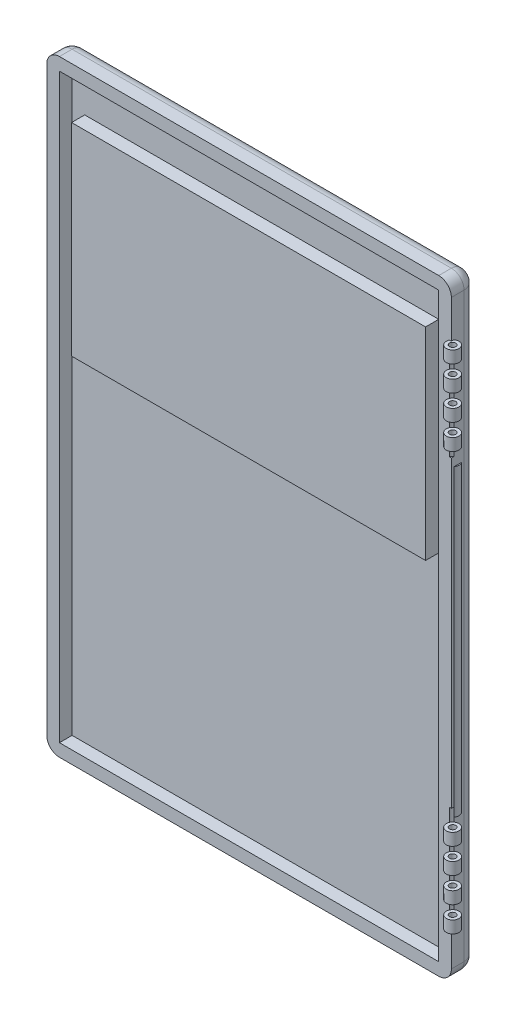
SolidWorks part; units mm, degrees
ref_plane "Frontal Plane" through (0, 0, 0) normal (0, 0, 1) x (1, 0, 0)
ref_plane "Horizontal Plane" through (0, 0, 0) normal (0, 1, 0) x (1, 0, 0)
ref_plane "Profile Plane" through (0, 0, 0) normal (1, 0, 0) x (0, 0, -1)
sketch "Sketch1" plane through (0, 0, 0) normal (0, 0, 1) x (1, 0, 0)
  line L1 (101.6, -152.4) -> (-101.6, -152.4)
  line L2 (101.6, -152.4) -> (101.6, 152.4)
  line L3 (101.6, 152.4) -> (-101.6, 152.4)
  line L4 (-101.6, -152.4) -> (-101.6, 152.4)
  line L5 (101.6, -152.4) -> (-101.6, 152.4) construction
  line L6 (101.6, 152.4) -> (-101.6, -152.4) construction
  point P0 (0, 0)
  dimension "D1" = 203.2
  dimension "D2" = 304.8
extrude "Boss-Extrude1" add sketch "Sketch1" against normal blind 12.7
ref_plane "Plane5" through (0, 0, 1.27) normal (0, 0, 1) x (1, 0, 0)
fillet "Fillet1" radius 6.35 8 edges at (-101.6, -152.4, -6.35) (0, -152.4, -12.7) (101.6, -152.4, -6.35) (-101.6, 0, -12.7) (101.6, 152.4, -6.35) (101.6, 0, -12.7) (-101.6, 152.4, -6.35) (0, 152.4, -12.7)
sketch "Sketch2" plane through (0, 0, 0) normal (0, 0, 1) x (1, 0, 0)
  line L0 (95.25, 152.4) -> (-95.25, 152.4) construction
  line L1 (95.25, -146.05) -> (-95.25, -146.05)
  line L2 (95.25, -146.05) -> (95.25, 146.05)
  line L3 (95.25, 146.05) -> (-95.25, 146.05)
  line L4 (-95.25, -146.05) -> (-95.25, 146.05)
  line L5 (95.25, -146.05) -> (-95.25, 146.05) construction
  line L6 (95.25, 146.05) -> (-95.25, -146.05) construction
  line L7 (-101.6, 146.05) -> (-101.6, -146.05) construction
  point P0 (0, 0)
  dimension "D1" = 6.35
  dimension "D2" = 6.35
extrude "Cut-Extrude1" cut sketch "Sketch2" against normal blind 6.35
sketch "Sketch3" plane through (0, 0, 0) normal (0, 1, 0) x (1, 0, 0)
  line L0 (95.25, 0) -> (101.6, 0) construction
  circle A0 centre (103.505, -1.27) radius 3.175
  dimension "D1" = 6.35
  dimension "D2" = 1.27
  dimension "D3" = 103.505
extrude "Boss-Extrude3" add sketch "Sketch3" along normal mid plane 254
sketch "Sketch14" plane through (0, 127, 0) normal (0, 1, 0) x (1, 0, 0)
  circle A0 centre (103.505, -1.27) radius 1.5875
  circle A1 centre (103.505, -1.27) radius 3.175 construction
  dimension "D1" = 3.175
extrude "Cut-Extrude9" cut sketch "Sketch14" against normal offset from surface (252.73 mm away) 1.27 up to face at (102.8974, -127, 0.8684)
sketch "Sketch6" plane through (0, 0, 1.27) normal (0, 0, 1) x (1, 0, 0)
  line L0 (106.68, -127) -> (106.68, 127) construction
  line L1 (103.505, 120.904) -> (106.68, 120.904)
  line L2 (103.505, 120.904) -> (103.505, 114.3)
  line L3 (103.505, 114.3) -> (106.68, 114.3)
  line L4 (106.68, 120.904) -> (106.68, 114.3)
  line L5 (103.505, 132.7034) -> (103.505, -150.9112) construction
  line L6 (103.505, -95.504) -> (106.68, -95.504)
  line L7 (103.505, 108.204) -> (106.68, 108.204)
  line L8 (103.505, 108.204) -> (103.505, 101.6)
  line L9 (103.505, 101.6) -> (106.68, 101.6)
  line L10 (106.68, 108.204) -> (106.68, 101.6)
  line L11 (103.505, 95.504) -> (106.68, 95.504)
  line L12 (103.505, 95.504) -> (103.505, 88.9)
  line L13 (103.505, 88.9) -> (106.68, 88.9)
  line L14 (106.68, 95.504) -> (106.68, 88.9)
  line L15 (103.505, -120.904) -> (106.68, -120.904)
  line L16 (103.505, -120.904) -> (103.505, -114.3)
  line L17 (103.505, -114.3) -> (106.68, -114.3)
  line L18 (106.68, -120.904) -> (106.68, -114.3)
  line L19 (103.505, -108.204) -> (106.68, -108.204)
  line L20 (103.505, -108.204) -> (103.505, -101.6)
  line L21 (103.505, -101.6) -> (106.68, -101.6)
  line L22 (106.68, -108.204) -> (106.68, -101.6)
  line L23 (103.505, -95.504) -> (103.505, -88.9)
  line L24 (103.505, -88.9) -> (106.68, -88.9)
  line L25 (106.68, -95.504) -> (106.68, -88.9)
  line L32 (103.505, -76.2) -> (106.68, -76.2)
  line L33 (103.505, -76.2) -> (103.505, -82.804)
  line L34 (103.505, -82.804) -> (106.68, -82.804)
  line L35 (106.68, -76.2) -> (106.68, -82.804)
  line L36 (103.505, 82.804) -> (106.68, 82.804)
  line L37 (103.505, 82.804) -> (103.505, 76.2)
  line L38 (103.505, 76.2) -> (106.68, 76.2)
  line L39 (106.68, 82.804) -> (106.68, 76.2)
  dimension "D1" = 6.604
  dimension "D2" = 6.096
  dimension "D3" = 114.3
  dimension "D4" = 6.096
  dimension "D6" = 101.6
  dimension "D9" = 88.9
  dimension "D11" = 3.175
  dimension "D12" = 114.3
  dimension "D14" = 101.6
  dimension "D16" = 88.9
revolve "Cut-Revolve1" cut sketch "Sketch6" angle 360 about L5
sketch "Sketch19" plane through (0, 0, 0) normal (0, 0, 1) x (1, 0, 0)
  line L1 (-95.25, 149.225) -> (95.25, 149.225)
  line L2 (-98.425, 146.05) -> (-98.425, -146.05)
  line L3 (-95.25, -149.225) -> (95.25, -149.225)
  line L4 (98.425, 146.05) -> (98.425, -146.05)
  line L5 (95.25, 152.4) -> (-95.25, 152.4) construction
  line L6 (-101.6, 146.05) -> (-101.6, -146.05) construction
  line L7 (101.6, 127) -> (101.6, 146.05) construction
  line L8 (-95.25, -152.4) -> (95.25, -152.4) construction
  arc A0 (98.425, 146.05) -> (95.25, 149.225) centre (95.25, 146.05) ccw
  arc A1 (-95.25, 149.225) -> (-98.425, 146.05) centre (-95.25, 146.05) ccw
  arc A2 (98.425, -146.05) -> (95.25, -149.225) centre (95.25, -146.05) cw
  arc A3 (-95.25, -149.225) -> (-98.425, -146.05) centre (-95.25, -146.05) cw
  dimension "D5" = 3.175
  dimension "D1" = 3.175
  dimension "D2" = 3.175
  dimension "D3" = 3.175
  dimension "D4" = 3.175
sketch "Sketch21" plane through (0, 0, 1.27) normal (0, 0, 1) x (1, 0, 0)
  line L0 (101.6, 127) -> (101.6, 146.05) construction
  line L1 (101.6, 76.2) -> (106.045, 76.2)
  line L2 (101.6, 76.2) -> (101.6, -76.2)
  line L3 (101.6, -76.2) -> (106.045, -76.2)
  line L4 (106.045, 76.2) -> (106.045, -76.2)
  line L7 (106.68, 76.2) -> (100.33, 76.2) construction
  line L9 (100.33, -76.2) -> (106.68, -76.2) construction
  dimension "D2" = 4.445
extrude "Cut-Extrude14" cut sketch "Sketch21" against normal through all both and the other way through all
sketch "Sketch22" plane through (0, 0, 0) normal (1, 0, 0) x (0, 0, -1)
  line L0 (0, 127) -> (0, 146.05) construction
  line L1 (-3.81, 76.2) -> (0, 76.2)
  line L2 (-3.81, 76.2) -> (-3.81, -76.2)
  line L3 (-3.81, -76.2) -> (0, -76.2)
  line L4 (0, 76.2) -> (0, -76.2)
  line L5 (1.27, -76.2) -> (-3.81, -76.2) construction
  line L6 (1.27, 76.2) -> (-3.81, 76.2) construction
  line L7 (-3.81, -76.2) -> (-3.81, 76.2) construction
extrude "Cut-Extrude15" cut sketch "Sketch22" against normal through all both and the other way through all
sketch "Sketch24" plane through (0, 0, -6.35) normal (0, 0, 1) x (1, 0, 0)
  line L0 (95.25, 152.4) -> (-95.25, 152.4) construction
  line L1 (-88.9, 127) -> (88.9, 127)
  line L2 (-88.9, 127) -> (-88.9, 25.4)
  line L3 (-88.9, 25.4) -> (88.9, 25.4)
  line L4 (88.9, 127) -> (88.9, 25.4)
  line L5 (-101.6, 146.05) -> (-101.6, -146.05) construction
  dimension "D1" = 25.4
  dimension "D2" = 12.7
  dimension "D3" = 177.8
  dimension "D4" = 101.6
extrude "Boss-Extrude5" add sketch "Sketch24" along normal mid plane 13.208
